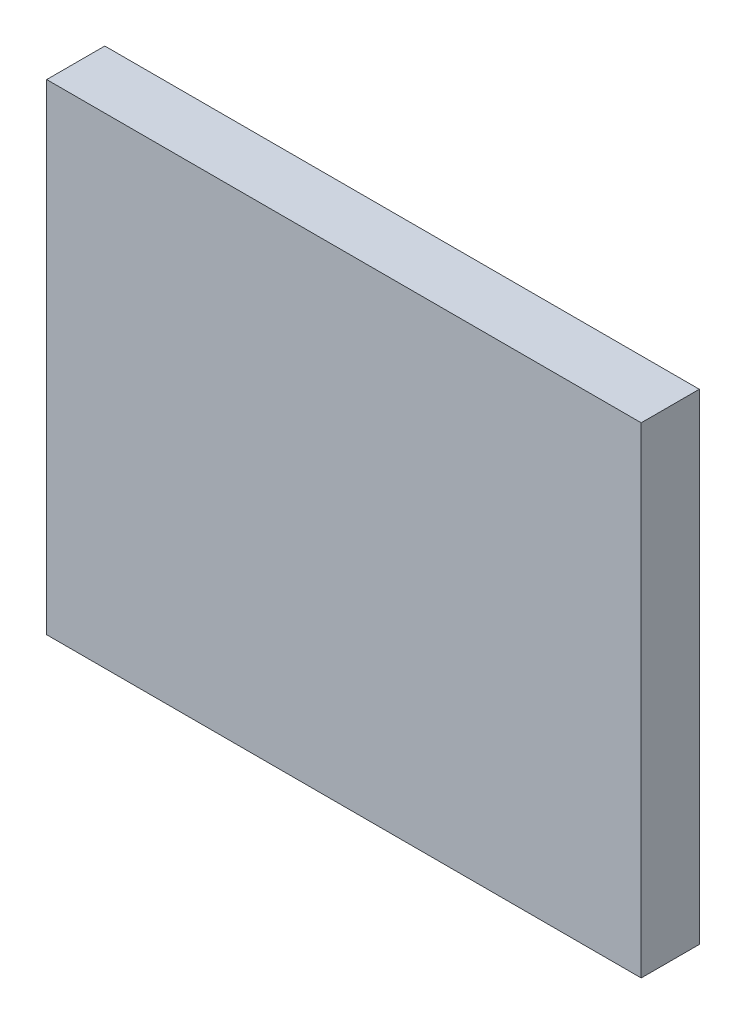
SolidWorks part; units mm, degrees
ref_plane "前视基准面" through (0, 0, 0) normal (0, 0, 1) x (1, 0, 0)
ref_plane "上视基准面" through (0, 0, 0) normal (0, 1, 0) x (1, 0, 0)
ref_plane "右视基准面" through (0, 0, 0) normal (1, 0, 0) x (0, 0, -1)
sketch "草图1" plane through (0, 0, 0) normal (0, 0, 1) x (1, 0, 0)
  line L1 (-77.0988, 37.607) -> (25.2209, 37.607)
  line L2 (-77.0988, 37.607) -> (-77.0988, -45.1463)
  line L3 (-77.0988, -45.1463) -> (25.2209, -45.1463)
  line L4 (25.2209, 37.607) -> (25.2209, -45.1463)
extrude "凸台-拉伸1" add sketch "草图1" along normal blind 10
